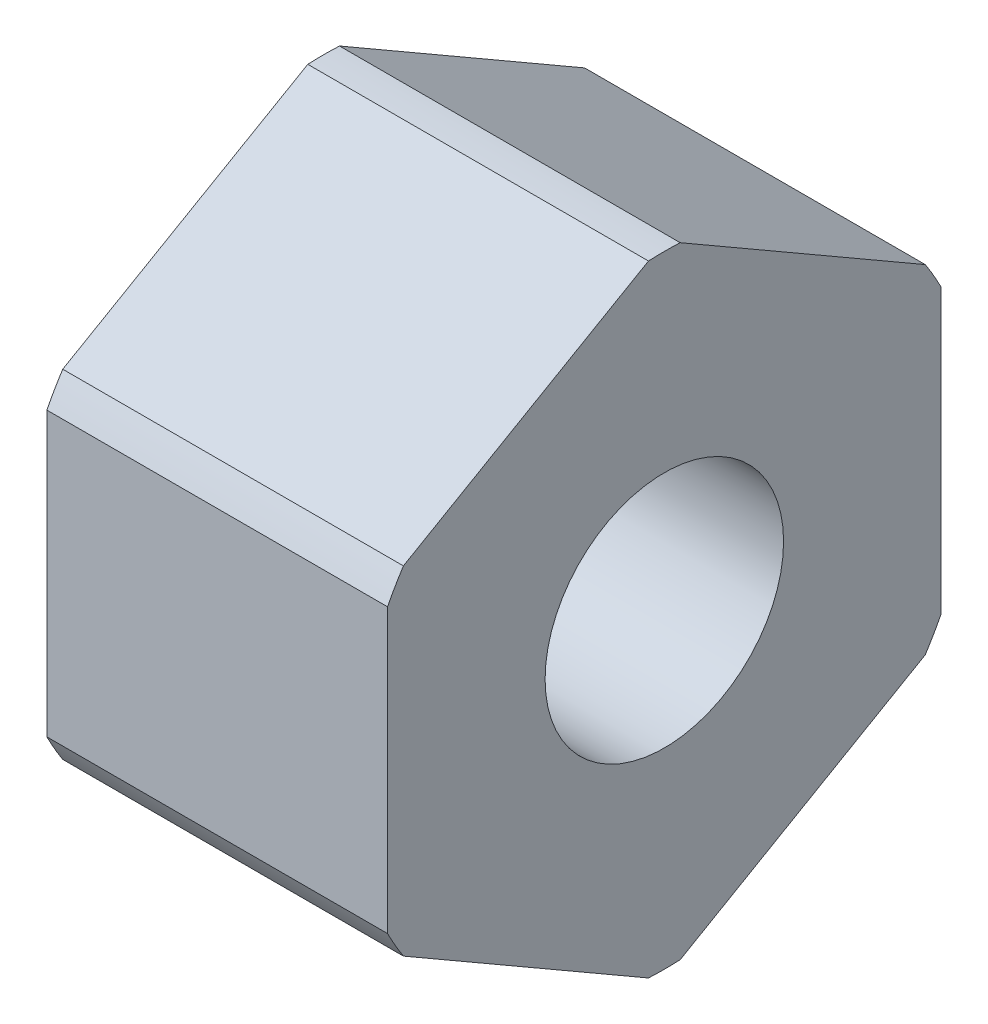
SolidWorks part; units mm, degrees
ref_plane "前视基准面" through (0, 0, 0) normal (0, 0, 1) x (1, 0, 0)
ref_plane "上视基准面" through (0, 0, 0) normal (0, 1, 0) x (1, 0, 0)
ref_plane "右视基准面" through (0, 0, 0) normal (1, 0, 0) x (0, 0, -1)
sketch "草图1" plane through (0, 0, 0) normal (0, 0, 1) x (1, 0, 0)
  line L0 (-9.4054, 0) -> (5.4208, 0) construction
  line L1 (0, 10.1158) -> (0, -7.9228) construction
  line L2 (0, 1.4) -> (0, 3.65)
  line L3 (0, 3.65) -> (-4, 3.65)
  line L4 (-4, 3.65) -> (-4, 2.1)
  line L5 (-4, 2.1) -> (-3, 2.1)
  line L6 (-3, 2.1) -> (-3, 1.4)
  line L7 (-3, 1.4) -> (0, 1.4)
  dimension "D1" = 4
  dimension "D2" = 1
  dimension "D3" = 2.8
  dimension "D4" = 4.2
  dimension "D5" = 7.3
revolve "旋转1" add sketch "草图1" angle 360 about L0
sketch "草图2" plane through (-4, 0, 0) normal (-1, 0, 0) x (0, 0, 1)
  line L1 (0, 3.7528) -> (-3.25, 1.8764)
  line L2 (-3.25, 1.8764) -> (-3.25, -1.8764)
  line L3 (-3.25, -1.8764) -> (0, -3.7528)
  line L4 (0, -3.7528) -> (3.25, -1.8764)
  line L5 (3.25, -1.8764) -> (3.25, 1.8764)
  line L6 (3.25, 1.8764) -> (0, 3.7528)
  circle A0 centre (0, 0) radius 3.25 construction
  dimension "D1" = 6.5
extrude "切除-拉伸1" cut sketch "草图2" against normal blind 10 flip side to cut
